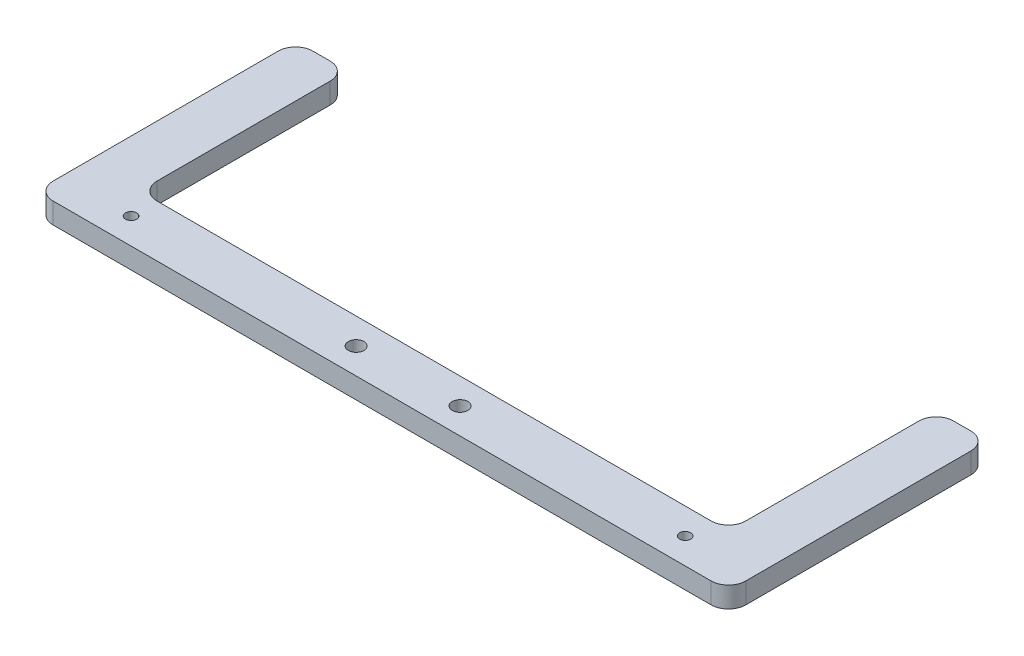
SolidWorks part; units mm, degrees
ref_plane "Front Plane" through (0, 0, 0) normal (0, 0, 1) x (1, 0, 0)
ref_plane "Top Plane" through (0, 0, 0) normal (0, 1, 0) x (1, 0, 0)
ref_plane "Right Plane" through (0, 0, 0) normal (1, 0, 0) x (0, 0, -1)
sketch "Sketch1" plane through (0, 0, 0) normal (0, 1, 0) x (1, 0, 0)
  line L0 (0, 0) -> (-85, 0)
  line L1 (-85, 0) -> (-85, 60)
  line L2 (-85, 60) -> (-100, 60)
  line L3 (-100, 60) -> (-100, -15)
  line L4 (-100, -15) -> (0, -15)
  line L5 (0, -15) -> (0, 0)
  dimension "D1" = 100
  dimension "D2" = 60
  dimension "D3" = 15
extrude "Boss-Extrude1" add sketch "Sketch1" along normal blind 6
fillet "Fillet1" radius 5 4 edges at (-100, 3, 15) (-100, 3, -60) (-85, 3, -60) (-85, 3, 0)
sketch "Sketch2" plane through (0, 6, 0) normal (0, 1, 0) x (1, 0, 0)
  line L0 (-15, 0) -> (-15, -15) construction
  line L1 (0, 0) -> (-80, 0) construction
  line L2 (-95, -15) -> (0, -15) construction
  circle A0 centre (-15, -7.5) radius 2.25
  circle A1 centre (-80, -7.5) radius 1.6
  dimension "D1" = 4.5
  dimension "D3" = 3.2
  dimension "D2" = 15
extrude "Cut-Extrude1" cut sketch "Sketch2" against normal through all
mirror "Mirror1" about plane through (0, 0, 0) normal (1, 0, 0) of "Cut-Extrude1", "Boss-Extrude1", "Fillet1"
